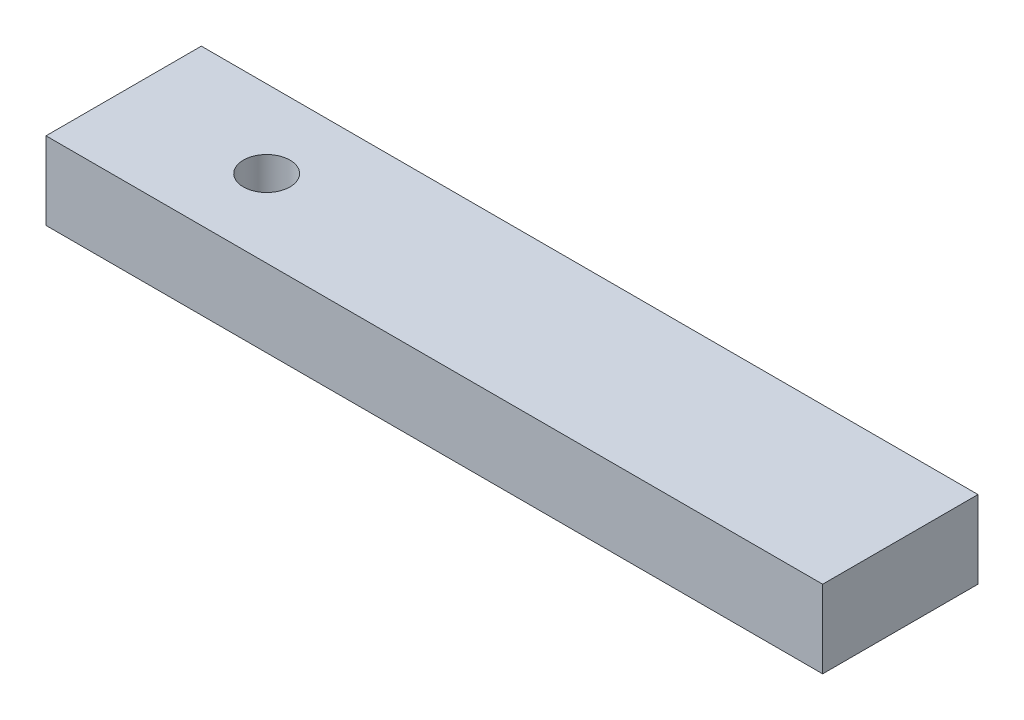
SolidWorks part; units mm, degrees
ref_plane "Ön Düzlem" through (0, 0, 0) normal (0, 0, 1) x (1, 0, 0)
ref_plane "Üst Düzlem" through (0, 0, 0) normal (0, 1, 0) x (1, 0, 0)
ref_plane "Sağ Düzlem" through (0, 0, 0) normal (1, 0, 0) x (0, 0, -1)
sketch "Çizim1" plane through (0, 0, 0) normal (0, 1, 0) x (1, 0, 0)
  line L1 (-50, 10) -> (50, 10)
  line L2 (-50, 10) -> (-50, -10)
  line L3 (-50, -10) -> (50, -10)
  line L4 (50, 10) -> (50, -10)
  point P0 (-5.5529, 3.8942)
  point P5 (0, 10)
  point P7 (-50, 0)
  dimension "D1" = 20
  dimension "D2" = 100
extrude "Yükseklik-Ekstrüzyon1" add sketch "Çizim1" along normal blind 10
sketch "Çizim2" plane through (0, 10, 0) normal (0, 1, 0) x (1, 0, 0)
  line L0 (50, 10) -> (-50, 10) construction
  circle A0 centre (-31.5892, 0) radius 3
  dimension "D1" = 6
  dimension "D2" = 10
extrude "Kes-Ekstrüzyon1" cut sketch "Çizim2" against normal through all
